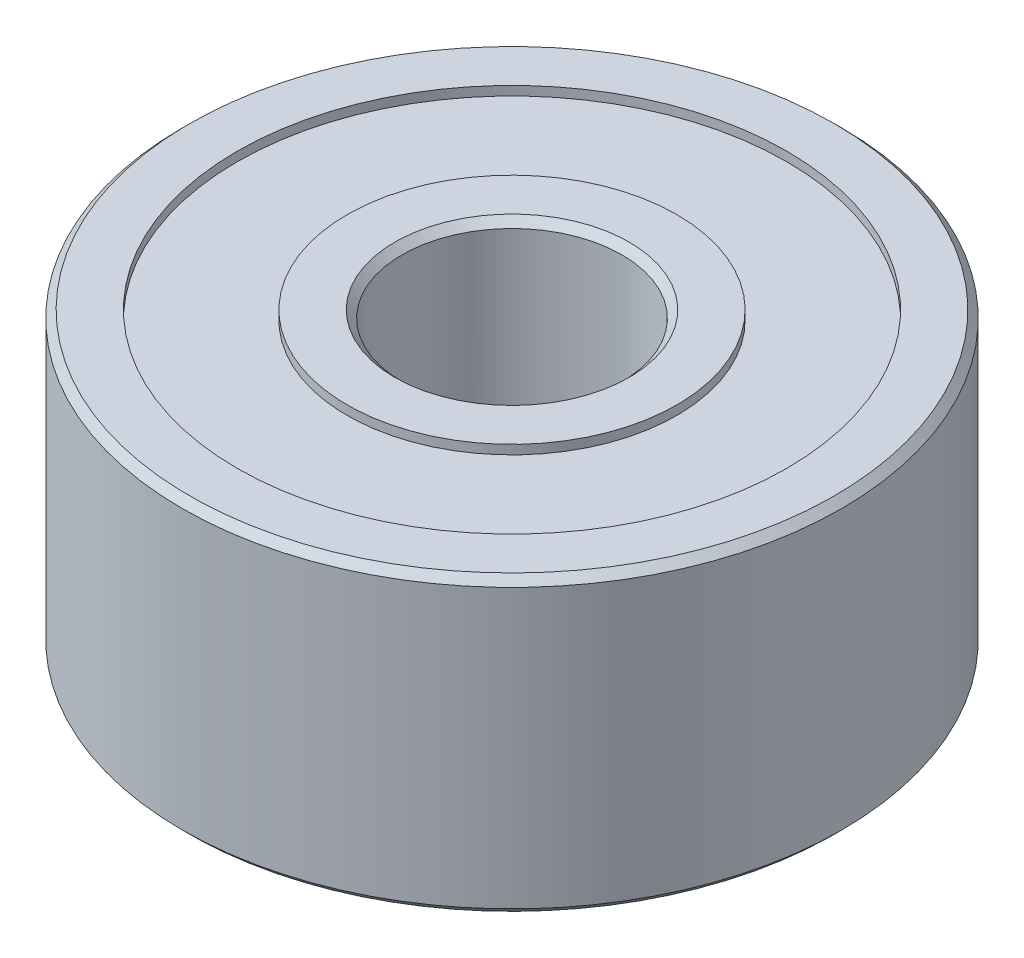
SolidWorks part; units mm, degrees
ref_plane "Front Plane" through (0, 0, 0) normal (0, 0, 1) x (1, 0, 0)
ref_plane "Top Plane" through (0, 0, 0) normal (0, 1, 0) x (1, 0, 0)
ref_plane "Right Plane" through (0, 0, 0) normal (1, 0, 0) x (0, 0, -1)
sketch "Sketch2" plane through (0, 0, 0) normal (0, 0, 1) x (1, 0, 0)
  line L12 (5.0269, 0) -> (0, 0) construction
  line L13 (1.5, 2) -> (1.5, -2)
  line L14 (4.5, -2) -> (1.5, -2) construction
  line L15 (4.5, -2) -> (4.5, 2) construction
  line L16 (4.5, 2) -> (1.5, 2) construction
  line L17 (1.5, -2) -> (1.5, 2) construction
  line L18 (4.5, -2) -> (1.5, 2) construction
  line L19 (4.5, 2) -> (1.5, -2) construction
  line L20 (1.5, -2) -> (2.25, -2)
  line L21 (2.25, -2) -> (2.25, -1.875)
  line L22 (2.25, -1.875) -> (3.75, -1.875)
  line L23 (3.75, -1.875) -> (3.75, -2)
  line L24 (3.75, -2) -> (4.5, -2)
  line L25 (4.5, -2) -> (4.5, 2)
  line L26 (4.5, 2) -> (3.75, 2)
  line L27 (3.75, 2) -> (3.75, 1.875)
  line L28 (3.75, 1.875) -> (2.25, 1.875)
  line L29 (2.25, 1.875) -> (2.25, 2)
  line L30 (2.25, 2) -> (1.5, 2)
  line L31 (0, -2) -> (0, 2) construction
  point P0 (3, 0)
  dimension "D1" = 1.5
  dimension "D2" = 4.5
  dimension "D3" = 4
  dimension "D4" = 0.75
  dimension "D5" = 0.75
  dimension "D6" = 0.125
revolve "Revolve1" add sketch "Sketch2" angle 360 about L31
chamfer "Chamfer1" distance 0.1 angle 45 4 edges at (0, -2, -1.5) (0, -2, -4.5) (0, 2, -1.5) (0, 2, -4.5)
